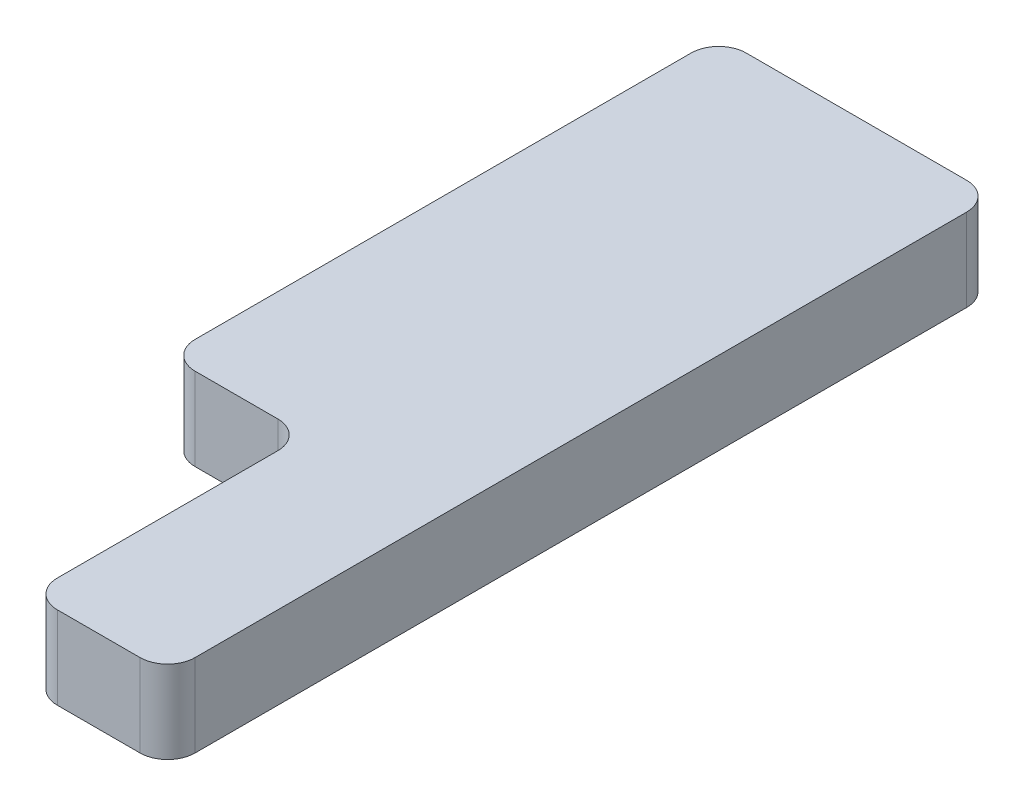
SolidWorks part; units mm, degrees
ref_plane "Plano frontal" through (0, 0, 0) normal (0, 0, 1) x (1, 0, 0)
ref_plane "Plano superior" through (0, 0, 0) normal (0, 1, 0) x (1, 0, 0)
ref_plane "Plano direito" through (0, 0, 0) normal (1, 0, 0) x (0, 0, -1)
sketch "Esboço1" plane through (0, 0, 0) normal (0, 1, 0) x (1, 0, 0)
  line L1 (-5, -15) -> (5, -15)
  line L2 (-5, -15) -> (-5, 15)
  line L3 (-5, 15) -> (5, 15)
  line L4 (5, -15) -> (5, 15)
  line L5 (-5, -15) -> (5, 15) construction
  line L6 (-5, 15) -> (5, -15) construction
  point P0 (0, 0)
  dimension "D1" = 10
  dimension "D2" = 30
extrude "Ressalto-extrusão1" add sketch "Esboço1" along normal blind 3
sketch "Esboço2" plane through (0, 3, 0) normal (0, 1, 0) x (1, 0, 0)
  line L1 (-5, -15) -> (0, -15)
  line L2 (-5, -15) -> (-5, -5)
  line L3 (-5, -5) -> (0, -5)
  line L4 (0, -15) -> (0, -5)
  dimension "D1" = 10
  dimension "D2" = 5
extrude "Corte-extrusão1" cut sketch "Esboço2" against normal blind 3
fillet "Filete1" radius 1 1 edges at (5, 1.5, 15)
fillet "Filete2" radius 1 1 edges at (0, 1.5, 15)
fillet "Filete3" radius 1 1 edges at (0, 1.5, 5)
fillet "Filete4" radius 1 1 edges at (-5, 1.5, 5)
fillet "Filete5" radius 1 1 edges at (-5, 1.5, -15)
fillet "Filete6" radius 1 1 edges at (5, 1.5, -15)
